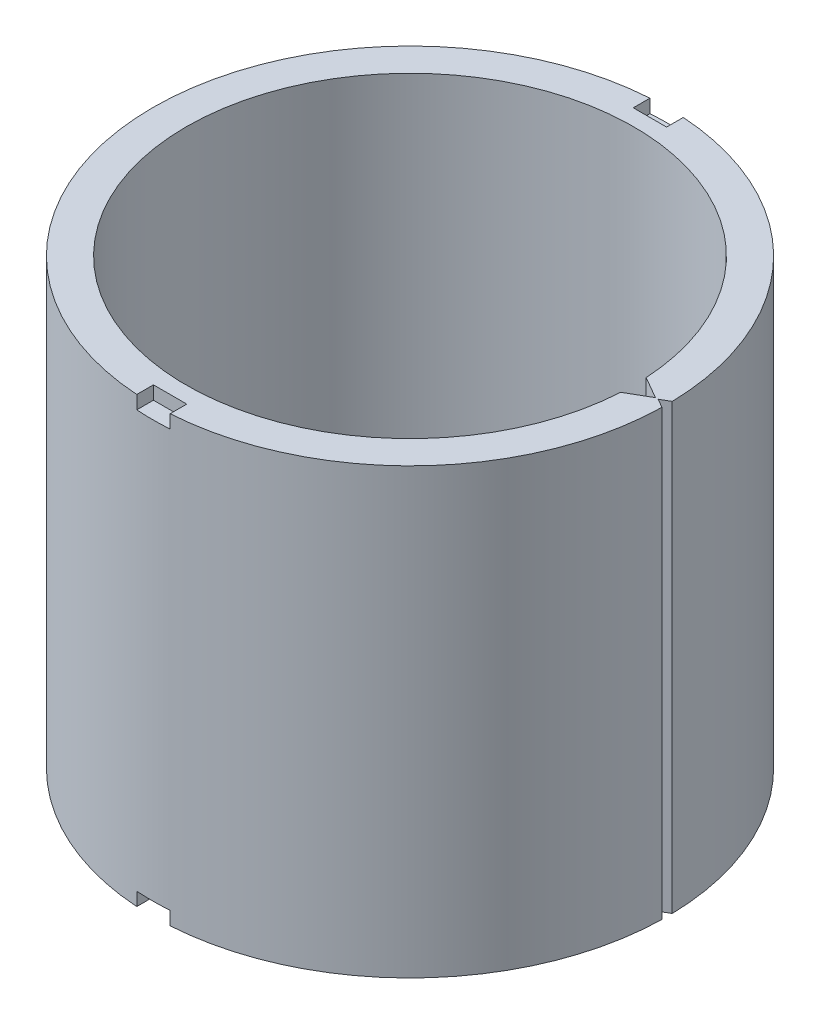
SolidWorks part; units mm, degrees
ref_plane "Front Plane" through (0, 0, 0) normal (0, 0, 1) x (1, 0, 0)
ref_plane "Top Plane" through (0, 0, 0) normal (0, 1, 0) x (1, 0, 0)
ref_plane "Right Plane" through (0, 0, 0) normal (1, 0, 0) x (0, 0, -1)
sketch "Sketch2" plane through (0, 0, 0) normal (0, 0, 1) x (1, 0, 0)
  line L0 (21.3024, 0) -> (21.3024, 42.2217)
  line L1 (18.8924, 0) -> (-18.8924, 0) construction
  line L2 (21.3024, 42.2217) -> (24.4774, 42.2217)
  line L3 (24.4774, 42.2217) -> (24.4774, 0)
  line L4 (0, 0) -> (16.51, 0)
  line L5 (16.51, 0) -> (17.1749, 38.0942)
  line L6 (17.1749, 38.0942) -> (0, 38.0942)
  line L7 (0, 38.0942) -> (0, 0)
  line L8 (0, 0) -> (16.51, 0) construction
  line L9 (16.51, 0) -> (17.1749, 38.0942) construction
  line L10 (17.1749, 38.0942) -> (0, 38.0942) construction
  line L11 (0, 38.0942) -> (0, 0) construction
  line L12 (24.4774, 0) -> (21.3024, 0)
  dimension "D2" = 4.1275
  dimension "D3" = 4.1275
  dimension "D4" = 3.175
  dimension "D1" = 0
revolve "Revolve1" add sketch "Sketch2" angle 360 about L11
sketch "Sketch3" plane through (0, 42.2217, 0) normal (0, 1, 0) x (1, 0, 0)
  line L0 (0, -23.342) -> (0, 23.342) construction
  line L1 (-1.5875, 26.0134) -> (1.5875, 26.0134)
  line L2 (-1.5875, 26.0134) -> (-1.5875, 22.8384)
  line L3 (-1.5875, 22.8384) -> (1.5875, 22.8384)
  line L4 (1.5875, 26.0134) -> (1.5875, 22.8384)
  line L5 (1.5875, -26.0134) -> (-1.5875, -26.0134)
  line L6 (1.5875, -26.0134) -> (1.5875, -22.8384)
  line L7 (1.5875, -22.8384) -> (-1.5875, -22.8384)
  line L8 (-1.5875, -26.0134) -> (-1.5875, -22.8384)
  circle A0 centre (0, 0) radius 24.4774 construction
  point P8 (0, -26.0134)
  point P11 (1.5875, 24.4259)
  point P14 (1.5875, -24.4259)
  point P15 (3.1802, -22.6825)
  dimension "D1" = 3.175
  dimension "D2" = 3.175
  dimension "D3" = 3.175
extrude "Cut-Extrude1" cut sketch "Sketch3" against normal blind 1.27
ref_plane "Plane4" through (0, 21.1108, 0) normal (0, 1, 0) x (1, 0, 0)
mirror "Mirror1" about plane through (0, 21.1108, 0) normal (0, 1, 0) of "Cut-Extrude1"
sketch "Sketch4" plane through (0, 21.1108, 0) normal (0, 1, 0) x (1, 0, 0)
  line L0 (24.4725, 0.491) -> (23.622, 0)
  line L1 (-26.7144, 0) -> (26.7144, 0) construction
  line L2 (23.622, 0) -> (24.4725, -0.491)
  line L3 (21.2679, 1.2125) -> (23.368, 0)
  line L4 (23.368, 0) -> (21.2679, -1.2125)
  circle A0 centre (0, 0) radius 24.4774 construction
  arc A2 (1.5875, -24.4259) -> (1.5875, 24.4259) centre (0, 0) ccw construction
  arc A3 (1.5875, -24.4259) -> (1.5875, 24.4259) centre (0, 0) ccw construction
  circle A4 centre (0, 0) radius 21.3024 construction
  circle A5 centre (0, 0) radius 21.3024 construction
  arc A6 (21.2679, 1.2125) -> (21.2679, -1.2125) centre (0, 0) cw
  arc A7 (24.4725, 0.491) -> (24.4725, -0.491) centre (0, 0) cw
  dimension "D1" = 60
  dimension "D2" = 30
  dimension "D3" = 60
  dimension "D4" = 30
  dimension "D5" = 0.254
  dimension "D6" = 23.368
extrude "Cut-Extrude2" cut sketch "Sketch4" along normal through all both and the other way through all
